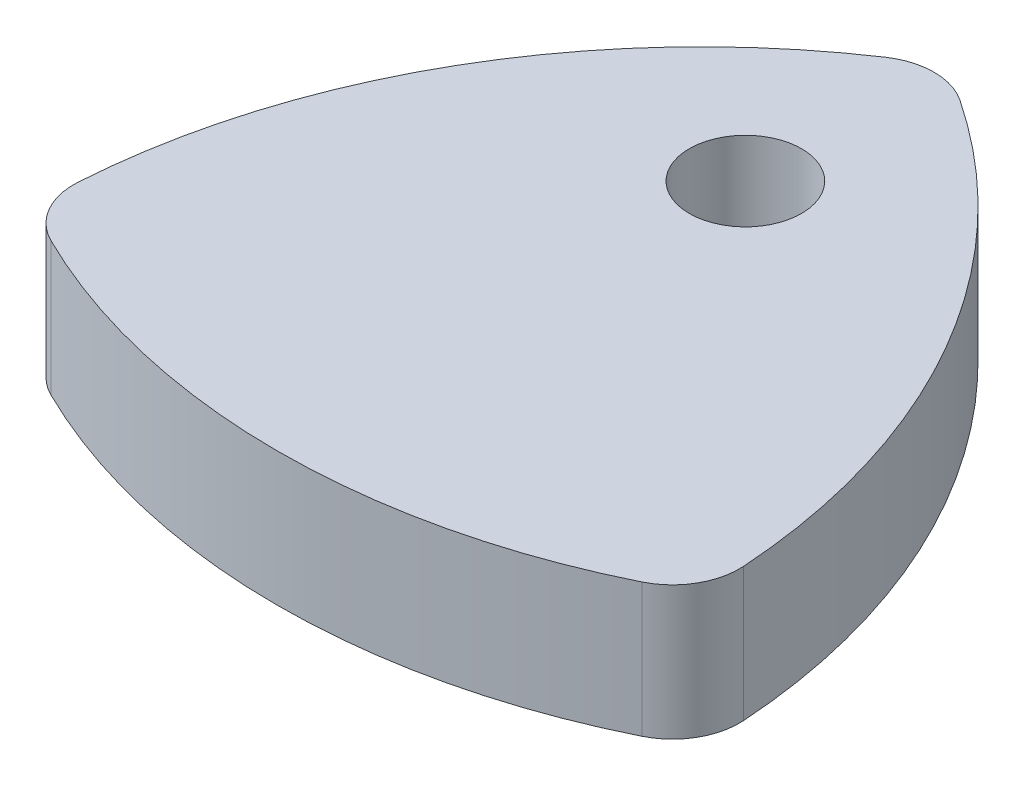
SolidWorks part; units mm, degrees
ref_plane "前视基准面" through (0, 0, 0) normal (0, 0, 1) x (1, 0, 0)
ref_plane "上视基准面" through (0, 0, 0) normal (0, 1, 0) x (1, 0, 0)
ref_plane "右视基准面" through (0, 0, 0) normal (1, 0, 0) x (0, 0, -1)
other "Configuration Table"
sketch "草图1" plane through (0, 0, 0) normal (0, 1, 0) x (1, 0, 0)
  line L0 (3.2989, 24.1149) -> (3.2989, -49975.8851) construction
  arc A0 (-21.7011, -19.1863) -> (28.2989, -19.1863) centre (3.2989, 24.1149) ccw
  arc A1 (3.2989, 24.1149) -> (-21.7011, -19.1863) centre (28.2989, -19.1863) ccw
  arc A2 (28.2989, -19.1863) -> (3.2989, 24.1149) centre (-21.7011, -19.1863) ccw
  dimension "D2" = 50
extrude "凸台-拉伸1" add sketch "草图1" along normal blind 10
sketch "草图2" plane through (0, 10, 0) normal (0, 1, 0) x (1, 0, 0)
  line L0 (-21.7011, -19.1863) -> (28.2989, -19.1863) construction
  line L1 (3.2989, 24.1149) -> (3.2989, -19.1863) construction
  circle A0 centre (3.2989, 9.1149) radius 4.2
  dimension "D1" = 15
extrude "切除-拉伸1" cut sketch "草图2" against normal through all
fillet "圆角1" radius 5 1 edges at (3.2989, 5, -24.1149)
fillet "圆角2" radius 5 1 edges at (-21.7011, 5, 19.1863)
fillet "圆角3" radius 5 1 edges at (28.2989, 5, 19.1863)
